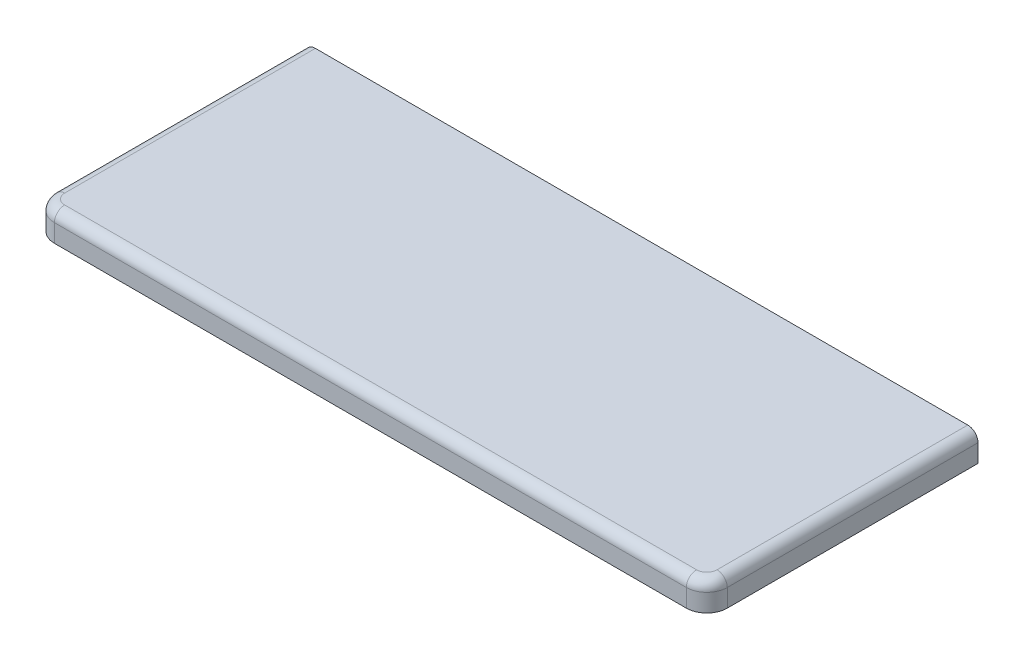
SolidWorks part; units mm, degrees
ref_plane "Front Plane" through (0, 0, 0) normal (0, 0, 1) x (1, 0, 0)
ref_plane "Top Plane" through (0, 0, 0) normal (0, 1, 0) x (1, 0, 0)
ref_plane "Right Plane" through (0, 0, 0) normal (1, 0, 0) x (0, 0, -1)
sketch "Sketch1" plane through (0, 0, 0) normal (0, 1, 0) x (1, 0, 0)
  line L1 (-32.875, -19) -> (32.875, -19)
  line L2 (-32.875, -19) -> (-32.875, 19)
  line L3 (-32.875, 19) -> (32.875, 19)
  line L4 (32.875, -19) -> (32.875, 19)
  line L5 (-32.875, -19) -> (32.875, 19) construction
  line L6 (-32.875, 19) -> (32.875, -19) construction
  point P0 (0, 0)
  dimension "D1" = 65.75
  dimension "D2" = 38
extrude "Boss-Extrude1" add sketch "Sketch1" along normal blind 2.75
sketch "Sketch3" plane through (0, 2.75, 0) normal (0, 1, 0) x (1, 0, 0)
  line L0 (32.875, 19) -> (-32.875, 19) construction
  line L15 (-32.875, 19) -> (32.875, 19)
  line L16 (-32.875, 19) -> (-32.875, 7.5)
  line L17 (-32.875, 7.5) -> (32.875, 7.5)
  line L18 (32.875, 19) -> (32.875, 7.5)
  line L19 (32.875, -19) -> (32.875, 19) construction
  line L21 (-32.875, 19) -> (-32.875, -19) construction
  dimension "D8" = 11.5
extrude "Cut-Extrude1" cut sketch "Sketch3" against normal through all
fillet "Fillet1" radius 2 2 edges at (-32.875, 1.375, 19) (32.875, 1.375, 19)
fillet "Fillet2" radius 1 5 edges at (32.875, 2.75, 4.75) (32.2892, 2.75, 18.4142) (0, 2.75, 19) (-32.2892, 2.75, 18.4142) (-32.875, 2.75, 4.75)
